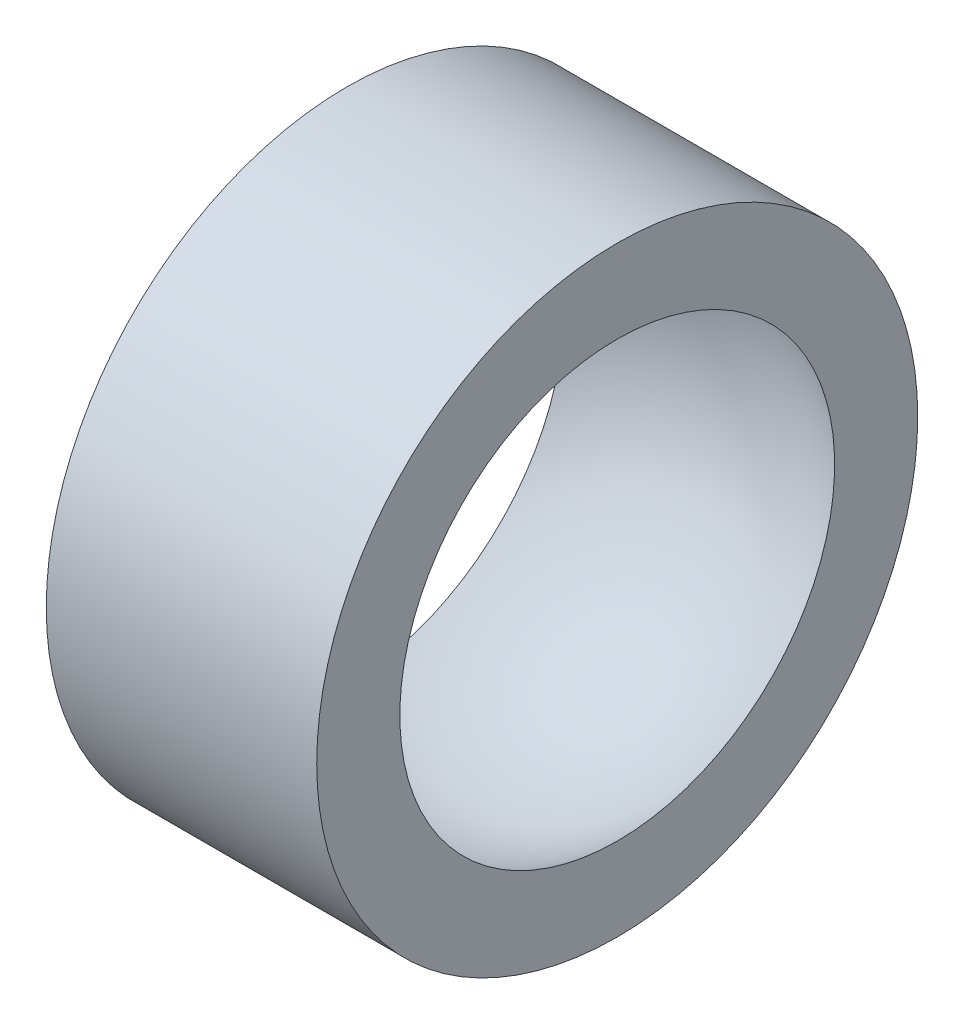
SolidWorks part; units mm, degrees
ref_plane "Front Plane" through (0, 0, 0) normal (0, 0, 1) x (1, 0, 0)
ref_plane "Top Plane" through (0, 0, 0) normal (0, 1, 0) x (1, 0, 0)
ref_plane "Right Plane" through (0, 0, 0) normal (1, 0, 0) x (0, 0, -1)
sketch "Sketch1" plane through (0, 0, 0) normal (0, 0, 1) x (1, 0, 0)
  line L0 (0, 0) -> (0, 50000) construction
  line L1 (0, 0) -> (50000, 0) construction
  line L3 (-3.375, -7.5) -> (3.375, -7.5)
  line L4 (-3.375, -7.5) -> (-3.375, 7.5)
  line L5 (-3.375, 7.5) -> (3.375, 7.5)
  line L6 (3.375, -7.5) -> (3.375, 7.5)
  line L7 (-3.375, -7.5) -> (3.375, 7.5) construction
  line L8 (-3.375, 7.5) -> (3.375, -7.5) construction
  circle A0 centre (0, 0) radius 6.39
  point P5 (0, 0)
  dimension "D3" = 12.78
  dimension "D1" = 6.75
  dimension "D2" = 15
revolve "Revolve1" add sketch "Sketch1" angle 360 about L1
